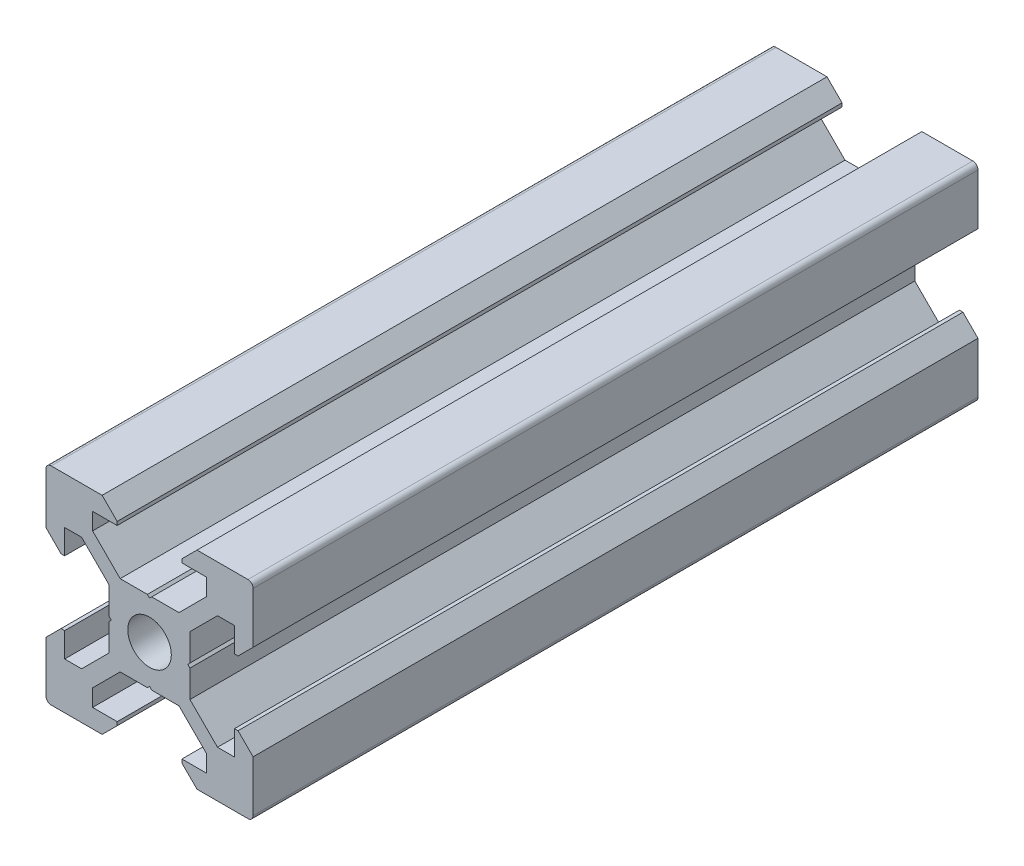
SolidWorks part; units mm, degrees
ref_plane "Plano frontal" through (0, 0, 0) normal (0, 0, 1) x (1, 0, 0)
ref_plane "Plano superior" through (0, 0, 0) normal (0, 1, 0) x (1, 0, 0)
ref_plane "Plano direito" through (0, 0, 0) normal (1, 0, 0) x (0, 0, -1)
sketch "Esboço1" plane through (0, 0, 0) normal (0, 0, 1) x (1, 0, 0)
  line L0 (3.9, -0.21) -> (3.69, 0)
  line L1 (3.69, 0) -> (3.9, 0.21)
  line L2 (3.9, 0.21) -> (3.9, 2.8393)
  line L3 (3.9, 2.8393) -> (6.5607, 5.5)
  line L4 (6.5607, 5.5) -> (8.2, 5.5)
  line L5 (8.2, 5.5) -> (8.2, 3.125)
  line L6 (8.2, 3.125) -> (8.545, 3.125)
  line L7 (8.545, 3.125) -> (10, 4.58)
  line L8 (10, 4.58) -> (10, 9.5)
  line L9 (9.5, 10) -> (4.58, 10)
  line L10 (4.58, 10) -> (3.125, 8.545)
  line L11 (3.125, 8.545) -> (3.125, 8.2)
  line L12 (3.125, 8.2) -> (5.5, 8.2)
  line L13 (5.5, 8.2) -> (5.5, 6.5607)
  line L14 (5.5, 6.5607) -> (2.8393, 3.9)
  line L15 (2.8393, 3.9) -> (0.21, 3.9)
  line L16 (0.21, 3.9) -> (0, 3.69)
  line L17 (0, 3.69) -> (-0.21, 3.9)
  line L18 (-0.21, 3.9) -> (-2.8393, 3.9)
  line L19 (-2.8393, 3.9) -> (-5.5, 6.5607)
  line L20 (-5.5, 6.5607) -> (-5.5, 8.2)
  line L21 (-5.5, 8.2) -> (-3.125, 8.2)
  line L22 (-3.125, 8.2) -> (-3.125, 8.545)
  line L23 (-3.125, 8.545) -> (-4.58, 10)
  line L24 (-4.58, 10) -> (-9.5, 10)
  line L25 (-10, 9.5) -> (-10, 4.58)
  line L26 (-10, 4.58) -> (-8.545, 3.125)
  line L27 (-8.545, 3.125) -> (-8.2, 3.125)
  line L28 (-8.2, 3.125) -> (-8.2, 5.5)
  line L29 (-8.2, 5.5) -> (-6.5607, 5.5)
  line L30 (-6.5607, 5.5) -> (-3.9, 2.8393)
  line L31 (-3.9, 2.8393) -> (-3.9, 0.21)
  line L32 (-3.9, 0.21) -> (-3.69, 0)
  line L33 (-3.69, 0) -> (-3.9, -0.21)
  line L34 (-3.9, -0.21) -> (-3.9, -2.8393)
  line L35 (-3.9, -2.8393) -> (-6.5607, -5.5)
  line L36 (-6.5607, -5.5) -> (-8.2, -5.5)
  line L37 (-8.2, -5.5) -> (-8.2, -3.125)
  line L38 (-8.2, -3.125) -> (-8.545, -3.125)
  line L39 (-8.545, -3.125) -> (-10, -4.58)
  line L40 (-10, -4.58) -> (-10, -9.5)
  line L41 (-9.5, -10) -> (-4.58, -10)
  line L42 (-4.58, -10) -> (-3.125, -8.545)
  line L43 (-3.125, -8.545) -> (-3.125, -8.2)
  line L44 (-3.125, -8.2) -> (-5.5, -8.2)
  line L45 (-5.5, -8.2) -> (-5.5, -6.5607)
  line L46 (-5.5, -6.5607) -> (-2.8393, -3.9)
  line L47 (-2.8393, -3.9) -> (-0.21, -3.9)
  line L48 (-0.21, -3.9) -> (0, -3.69)
  line L49 (0, -3.69) -> (0.21, -3.9)
  line L50 (0.21, -3.9) -> (2.8393, -3.9)
  line L51 (2.8393, -3.9) -> (5.5, -6.5607)
  line L52 (5.5, -6.5607) -> (5.5, -8.2)
  line L53 (5.5, -8.2) -> (3.125, -8.2)
  line L54 (3.125, -8.2) -> (3.125, -8.545)
  line L55 (3.125, -8.545) -> (4.58, -10)
  line L56 (4.58, -10) -> (9.5, -10)
  line L57 (10, -9.5) -> (10, -4.58)
  line L58 (10, -4.58) -> (8.545, -3.125)
  line L59 (8.545, -3.125) -> (8.2, -3.125)
  line L60 (8.2, -3.125) -> (8.2, -5.5)
  line L61 (8.2, -5.5) -> (6.5607, -5.5)
  line L62 (6.5607, -5.5) -> (3.9, -2.8393)
  line L63 (3.9, -2.8393) -> (3.9, -0.21)
  circle A0 centre (0, 0) radius 2.1
  arc A1 (10, 9.5) -> (9.5, 10) centre (9.5, 9.5) ccw
  arc A2 (-9.5, 10) -> (-10, 9.5) centre (-9.5, 9.5) ccw
  arc A3 (-10, -9.5) -> (-9.5, -10) centre (-9.5, -9.5) ccw
  arc A4 (9.5, -10) -> (10, -9.5) centre (9.5, -9.5) ccw
extrude "Ressalto-extrusão1" add sketch "Esboço1" along normal blind 70
ref_plane "Plano1" through (0, 0, 0) normal (0, 1, 0) x (1, 0, 0)
ref_plane "Plano2" through (0, 0, 0) normal (1, 0, 0) x (0, 0, -1)
ref_plane "Plano3" through (0, 0, 35) normal (0, 0, 1) x (1, 0, 0)
